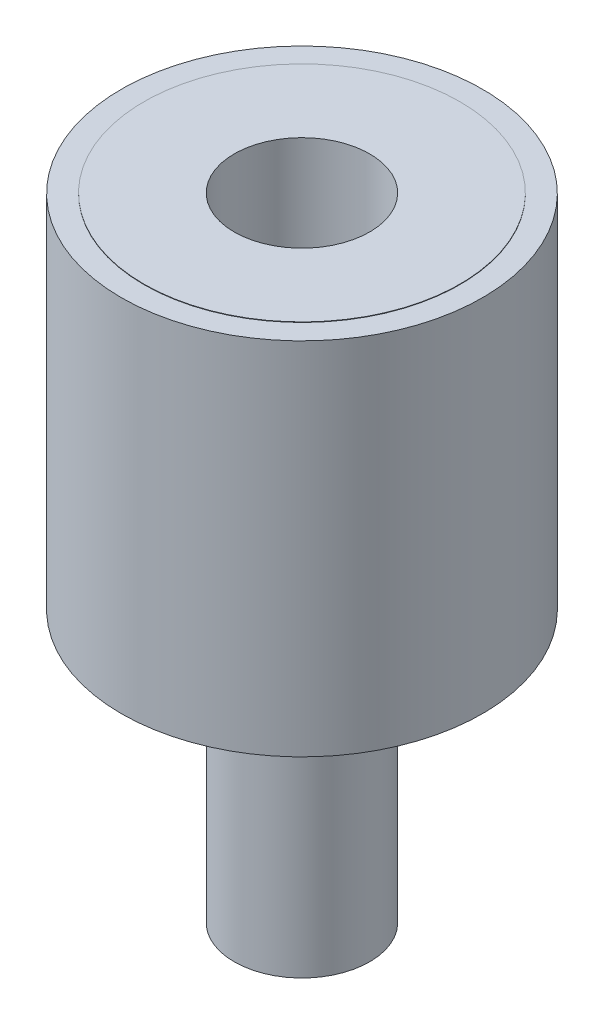
SolidWorks part; units mm, degrees
material "Rubber"
ref_plane "Front Plane" through (0, 0, 0) normal (0, 0, 1) x (1, 0, 0)
ref_plane "Top Plane" through (0, 0, 0) normal (0, 1, 0) x (1, 0, 0)
ref_plane "Right Plane" through (0, 0, 0) normal (1, 0, 0) x (0, 0, -1)
sketch "Sketch1" plane through (0, 0, 0) normal (0, 0, 1) x (1, 0, 0)
  line L0 (0, 5.5) -> (0, -5.5) construction
  line L1 (0, -5.5) -> (-1.5, -5.5)
  line L2 (-1.5, -5.5) -> (-1.5, 0.5)
  line L3 (-1.5, 0.5) -> (-3.5, 0.5)
  line L4 (-3.5, 0.5) -> (-3.5, 0.51)
  line L5 (-3.5, 0.51) -> (-4, 0.51)
  line L6 (-4, 0.51) -> (-4, 8.49)
  line L7 (-4, 8.49) -> (-3.5, 8.49)
  line L8 (-3.5, 8.49) -> (-3.5, 8.5)
  line L9 (-3.5, 8.5) -> (-1.5, 8.5)
  line L10 (-1.5, 8.5) -> (-1.5, 5.5)
  line L11 (-1.5, 5.5) -> (0, 5.5)
  line L12 (0, -5.5) -> (0, 5.5)
  line L13 (0, 0) -> (-2.8462, 0) construction
  dimension "D1" = 3
  dimension "D2" = 3
  dimension "D3" = 8
  dimension "D4" = 8
  dimension "D5" = 0.01
  dimension "D6" = 0.5
  dimension "D7" = 6
revolve "Revolve1" add sketch "Sketch1" angle 360 about L0
